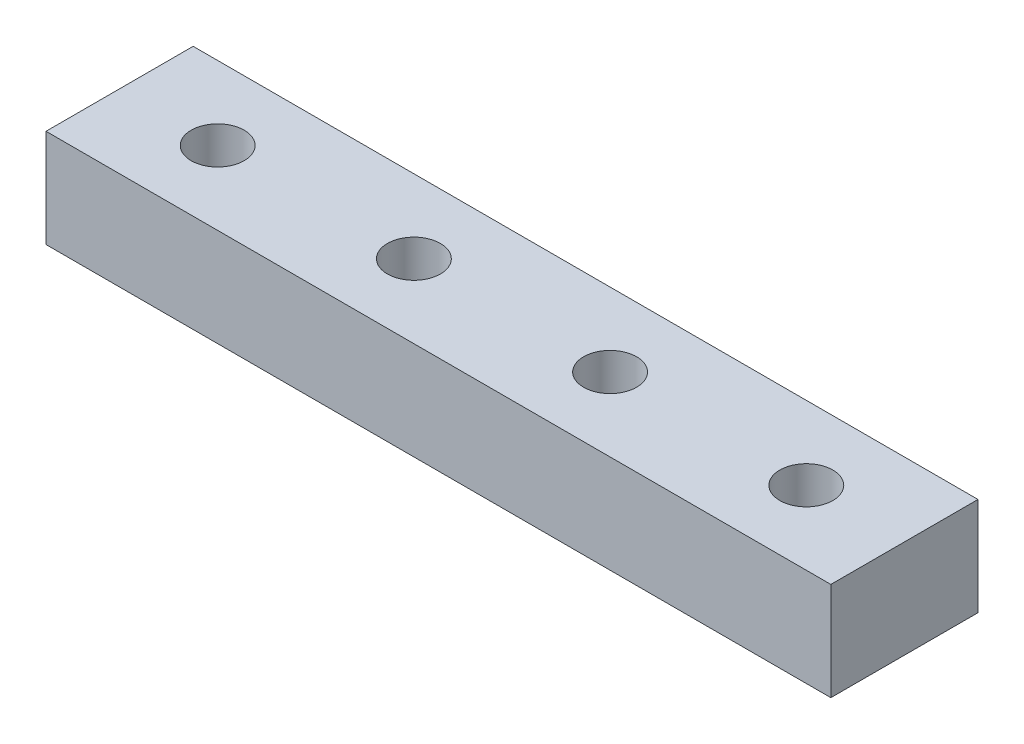
SolidWorks part; units mm, degrees
ref_plane "Front Plane" through (0, 0, 0) normal (0, 0, 1) x (1, 0, 0)
ref_plane "Top Plane" through (0, 0, 0) normal (0, 1, 0) x (1, 0, 0)
ref_plane "Right Plane" through (0, 0, 0) normal (1, 0, 0) x (0, 0, -1)
sketch "Sketch1" plane through (0, 0, 0) normal (0, 1, 0) x (1, 0, 0)
  line L1 (-50.8, 19.05) -> (50.8, 19.05)
  line L2 (-50.8, 19.05) -> (-50.8, 0)
  line L3 (-50.8, 0) -> (50.8, 0)
  line L4 (50.8, 19.05) -> (50.8, 0)
  point P4 (0, 0)
  dimension "D1" = 101.6
  dimension "D2" = 19.05
extrude "Boss-Extrude1" add sketch "Sketch1" along normal blind 12.7
sketch "Sketch2" plane through (0, 12.7, 0) normal (0, 1, 0) x (1, 0, 0)
  line L0 (-50.8, 9.525) -> (50.8, 9.525) construction
  line L1 (-50.8, 19.05) -> (-50.8, 0) construction
  line L2 (50.8, 0) -> (50.8, 19.05) construction
  circle A0 centre (-38.1, 9.525) radius 3.429
  circle A1 centre (38.1, 9.525) radius 3.429
  circle A2 centre (-12.7, 9.525) radius 3.429
  circle A3 centre (12.7, 9.525) radius 3.429
  dimension "D1" = 6.858
  dimension "D4" = 25.4
  dimension "D5" = 25.4
  dimension "D2" = 12.7
  dimension "D3" = 25.4
extrude "Cut-Extrude1" cut sketch "Sketch2" against normal through all
ref_plane "Plane1" through (0, 6.35, 0) normal (0, 1, 0) x (1, 0, 0)
sketch "Sketch3" plane through (0, 0, 0) normal (0, 1, 0) x (1, 0, 0)
  circle A0 centre (-12.7, 9.525) radius 6.604
  circle A1 centre (12.7, 9.525) radius 6.604
  circle A2 centre (-12.7, 9.525) radius 3.429 construction
  circle A3 centre (12.7, 9.525) radius 3.429 construction
  point P4 (0, 0)
  point P7 (0, 0)
  dimension "D1" = 13.208
extrude "Cut-Extrude4" cut sketch "Sketch3" along normal blind 6.985
